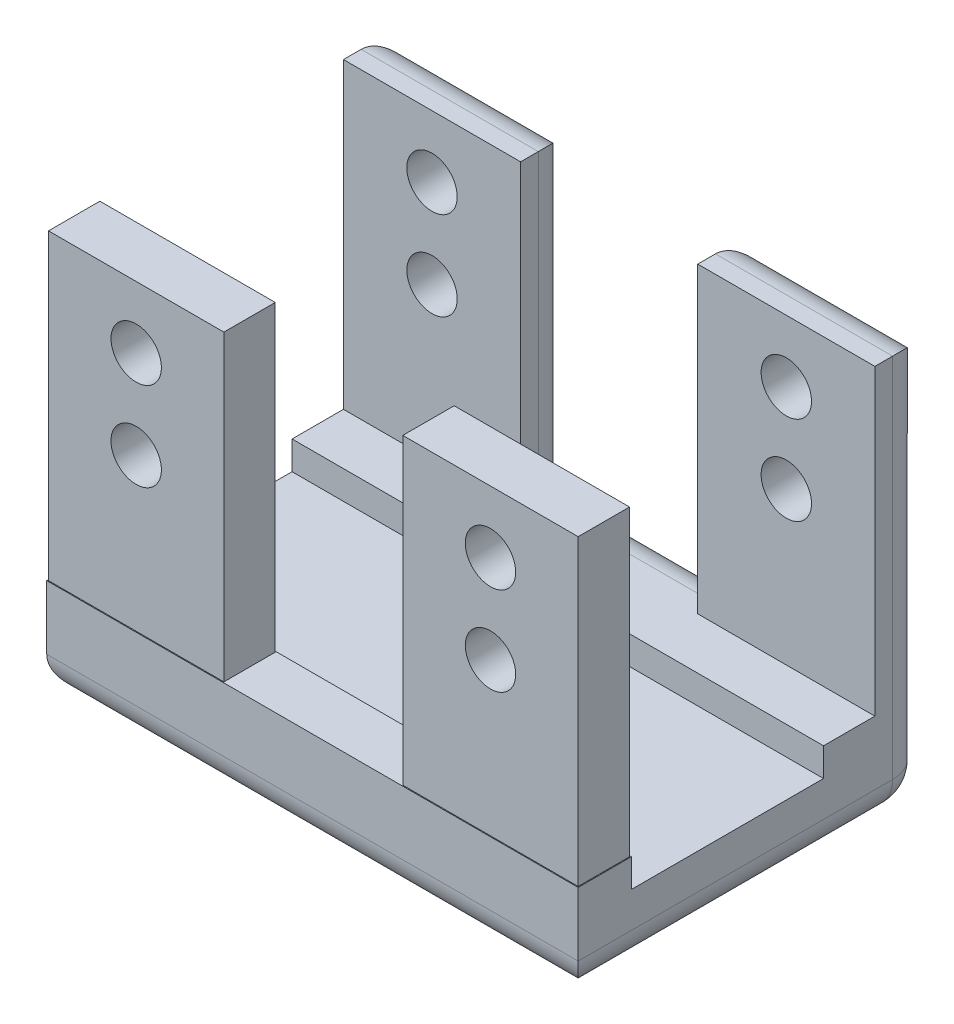
SolidWorks part; units mm, degrees
ref_plane "Front Plane" through (0, 0, 0) normal (0, 0, 1) x (1, 0, 0)
ref_plane "Top Plane" through (0, 0, 0) normal (0, 1, 0) x (1, 0, 0)
ref_plane "Right Plane" through (0, 0, 0) normal (1, 0, 0) x (0, 0, -1)
sketch "Sketch1" plane through (0, 0, 0) normal (0, 1, 0) x (1, 0, 0)
  line L1 (0, 0) -> (30, 0)
  line L2 (0, 0) -> (0, 19.75)
  line L3 (0, 19.75) -> (30, 19.75)
  line L4 (30, 0) -> (30, 19.75)
  dimension "D1" = 30
  dimension "D2" = 19.75
extrude "Boss-Extrude1" add sketch "Sketch1" along normal blind 4
sketch "Sketch2" plane through (0, 4, 0) normal (0, 1, 0) x (1, 0, 0)
  line L0 (30, 0) -> (30, 19.75) construction
  line L1 (0, 19.75) -> (30, 19.75)
  line L2 (0, 19.75) -> (0, 13.85)
  line L3 (0, 13.85) -> (30, 13.85)
  line L4 (30, 19.75) -> (30, 13.85)
  dimension "D1" = 5.9
extrude "Boss-Extrude2" add sketch "Sketch2" along normal blind 1.601
sketch "Sketch3" plane through (0, 4, 0) normal (0, 1, 0) x (1, 0, 0)
  line L1 (0, 0) -> (10, 0)
  line L2 (0, 0) -> (0, 3)
  line L3 (0, 3) -> (10, 3)
  line L4 (10, 0) -> (10, 3)
  line L5 (30, 0) -> (20, 0)
  line L6 (30, 0) -> (30, 3)
  line L7 (30, 3) -> (20, 3)
  line L8 (20, 0) -> (20, 3)
  dimension "D1" = 10
  dimension "D2" = 3
extrude "Boss-Extrude3" add sketch "Sketch3" along normal blind 18.7
sketch "Sketch4" plane through (0, 5.601, 0) normal (0, 1, 0) x (1, 0, 0)
  line L1 (0, 19.75) -> (10, 19.75)
  line L2 (0, 19.75) -> (0, 16.75)
  line L3 (0, 16.75) -> (10, 16.75)
  line L4 (10, 19.75) -> (10, 16.75)
  line L5 (30, 19.75) -> (20, 19.75)
  line L6 (30, 19.75) -> (30, 16.75)
  line L7 (30, 16.75) -> (20, 16.75)
  line L8 (20, 19.75) -> (20, 16.75)
  dimension "D1" = 10
  dimension "D2" = 3
extrude "Boss-Extrude4" add sketch "Sketch4" along normal blind 17.099
sketch "Sketch5" plane through (0, 4, 0) normal (0, 1, 0) x (1, 0, 0)
  line L1 (10, 3) -> (20, 3)
  line L2 (10, 3) -> (10, 0)
  line L3 (10, 0) -> (20, 0)
  line L4 (20, 3) -> (20, 0)
extrude "Boss-Extrude5" add sketch "Sketch5" along normal blind 1.601
fillet "Fillet1" radius 2 11 edges at (30, 11.35, -19.75) (25, 22.7, -19.75) (20, 14.1505, -19.75) (15, 5.601, -19.75) (10, 14.1505, -19.75) (5, 22.7, -19.75) (0, 11.35, -19.75) (15, 0, 0) (30, 0, -9.875) (15, 0, -19.75) (0, 0, -9.875)
sketch "Sketch6" plane through (0, 0, -16.75) normal (0, 0, 1) x (1, 0, 0)
  line L0 (0, 22.7) -> (10, 22.7) construction
  line L1 (5, 22.7) -> (5, 19.2) construction
  line L2 (10, 22.7) -> (20, 22.7) construction
  line L3 (15, 22.7) -> (15, 8.1156) construction
  circle A0 centre (5, 19.2) radius 1.4224
  circle A1 centre (25, 19.2) radius 1.4224
  circle A2 centre (5, 14.2) radius 1.4224
  circle A3 centre (25, 14.2) radius 1.4224
  dimension "D1" = 2.8448
  dimension "D2" = 3.5
  dimension "D3" = 2
extrude "Cut-Extrude1" cut sketch "Sketch6" against normal up to next
sketch "Sketch7" plane through (0, 0, -3) normal (0, 0, -1) x (-1, 0, 0)
  line L0 (-30, 22.7) -> (-20, 22.7) construction
  line L1 (-25, 22.7) -> (-25, 19.2) construction
  line L2 (-20, 22.7) -> (-10, 22.7) construction
  line L3 (-15, 22.7) -> (-15, 17.7883) construction
  circle A0 centre (-25, 19.2) radius 1.4224
  circle A1 centre (-5, 19.2) radius 1.4224
  circle A2 centre (-5, 14.2) radius 1.4224
  circle A3 centre (-25, 14.2) radius 1.4224
  dimension "D2" = 2.8448
  dimension "D1" = 3.5
  dimension "D3" = 2
extrude "Cut-Extrude2" cut sketch "Sketch7" against normal up to next
sketch "Sketch8" plane through (0, 22.7, 0) normal (0, 1, 0) x (1, 0, 0)
  line L0 (0, 1.5) -> (0.05, 1.5) construction
  line L1 (0, 3) -> (10, 3)
  line L2 (0, 3) -> (0, 0)
  line L3 (0, 0) -> (10, 0)
  line L4 (10, 3) -> (10, 0)
  line L5 (0.05, 2.95) -> (9.95, 2.95)
  line L6 (0.05, 2.95) -> (0.05, 0.05)
  line L7 (0.05, 0.05) -> (9.95, 0.05)
  line L8 (9.95, 2.95) -> (9.95, 0.05)
  line L9 (5, 3) -> (5, 2.95) construction
  line L10 (10, 0) -> (20, 0) construction
  line L11 (15, 0) -> (15, 4.7789) construction
  line L12 (20.05, 2.95) -> (20.05, 0.05)
  line L13 (29.95, 0.05) -> (20.05, 0.05)
  line L14 (20, 3) -> (20, 0)
  line L15 (30, 0) -> (20, 0)
  line L16 (25, 3) -> (25, 2.95) construction
  line L17 (30, 1.5) -> (29.95, 1.5) construction
  line L18 (29.95, 2.95) -> (29.95, 0.05)
  line L19 (29.95, 2.95) -> (20.05, 2.95)
  line L20 (30, 3) -> (30, 0)
  line L21 (30, 3) -> (20, 3)
  dimension "D1" = 0.05
  dimension "D2" = 0.05
  dimension "D3" = 2.9
  dimension "D4" = 9.9
extrude "Cut-Extrude3" cut sketch "Sketch8" against normal up to surface (17.099 mm away) up to face at (15, 5.601, -1.5)
